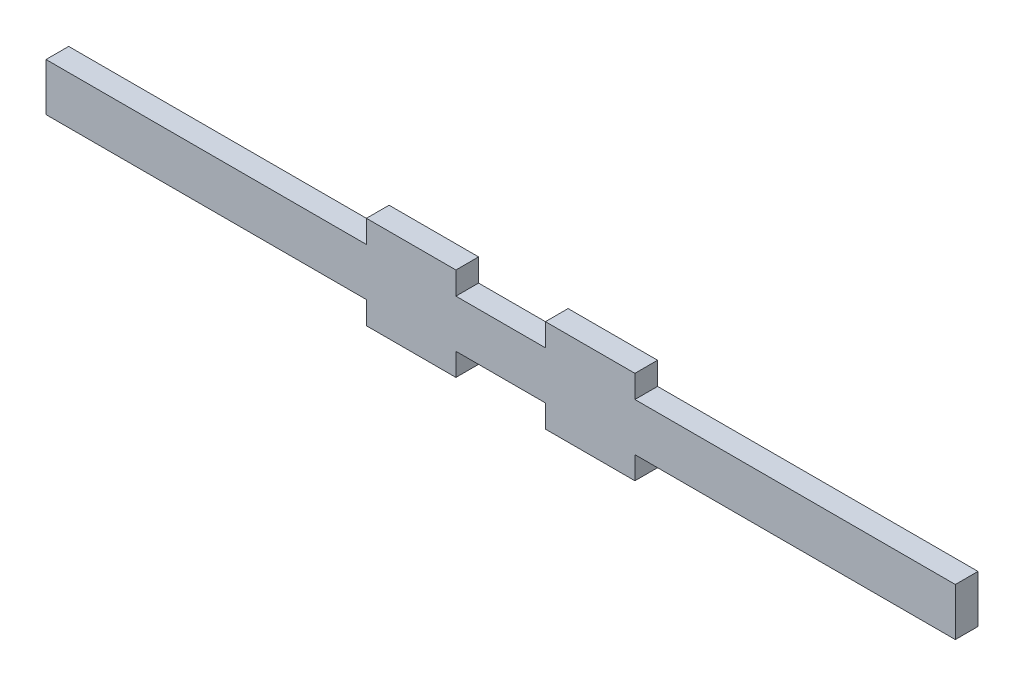
SolidWorks part; units mm, degrees
ref_plane "Front Plane" through (0, 0, 0) normal (0, 0, 1) x (1, 0, 0)
ref_plane "Top Plane" through (0, 0, 0) normal (0, 1, 0) x (1, 0, 0)
ref_plane "Right Plane" through (0, 0, 0) normal (1, 0, 0) x (0, 0, -1)
sketch "Sketch1" plane through (0, 0, 0) normal (0, 0, 1) x (1, 0, 0)
  line L1 (0, 0) -> (193.548, 0)
  line L2 (0, 0) -> (0, 19.812)
  line L3 (0, 19.812) -> (193.548, 19.812)
  line L4 (193.548, 0) -> (193.548, 19.812)
  dimension "D1" = 193.548
  dimension "D2" = 19.812
extrude "Base" add sketch "Sketch1" along normal blind 4.826
sketch "Sketch2" plane through (0, 0, 4.826) normal (0, 0, 1) x (1, 0, 0)
  line L0 (193.548, 19.812) -> (0, 19.812) construction
  line L1 (0, 19.812) -> (68.199, 19.812)
  line L2 (0, 19.812) -> (0, 14.986)
  line L3 (0, 14.986) -> (68.199, 14.986)
  line L4 (68.199, 19.812) -> (68.199, 14.986)
  line L5 (193.548, 19.812) -> (125.349, 19.812)
  line L6 (193.548, 19.812) -> (193.548, 14.986)
  line L7 (193.548, 14.986) -> (125.349, 14.986)
  line L8 (125.349, 19.812) -> (125.349, 14.986)
  line L9 (87.249, 19.812) -> (106.299, 19.812)
  line L10 (87.249, 19.812) -> (87.249, 14.986)
  line L11 (87.249, 14.986) -> (106.299, 14.986)
  line L12 (106.299, 19.812) -> (106.299, 14.986)
  line L13 (68.199, 14.986) -> (87.249, 14.986) construction
  line L14 (106.299, 14.986) -> (125.349, 14.986) construction
  line L15 (0, 9.906) -> (-50000, 9.906) construction
  line L16 (0, 19.812) -> (0, 0) construction
  line L17 (106.299, 4.826) -> (125.349, 4.826) construction
  line L18 (68.199, 4.826) -> (87.249, 4.826) construction
  line L19 (106.299, 0) -> (106.299, 4.826)
  line L20 (87.249, 4.826) -> (106.299, 4.826)
  line L21 (87.249, 0) -> (87.249, 4.826)
  line L22 (87.249, 0) -> (106.299, 0)
  line L23 (125.349, 0) -> (125.349, 4.826)
  line L24 (193.548, 4.826) -> (125.349, 4.826)
  line L25 (193.548, 0) -> (193.548, 4.826)
  line L26 (193.548, 0) -> (125.349, 0)
  line L27 (68.199, 0) -> (68.199, 4.826)
  line L28 (0, 4.826) -> (68.199, 4.826)
  line L29 (0, 0) -> (0, 4.826)
  line L30 (0, 0) -> (68.199, 0)
  point P20 (0, 9.906)
  dimension "D1" = 19.05
  dimension "D2" = 4.826
  dimension "D3" = 19.05
extrude "Tabs" cut sketch "Sketch2" against normal through all
equation "\"material\"= \"gmaterial@Forklift_v2.assembly\""
equation "\"tab\"= \"gtab@forklift_v2.assembly\""
equation "\"D1@Sketch1\"=8-2*\"material\""
equation "\"D1@Base\"=\"material\""
equation "\"D2@Sketch1\"=0.4+2*\"material\""
equation "\"D1@Sketch2\"=\"tab\""
equation "\"D2@Sketch2\"=\"material\""
equation "\"D3@Sketch2\"=\"tab\""
